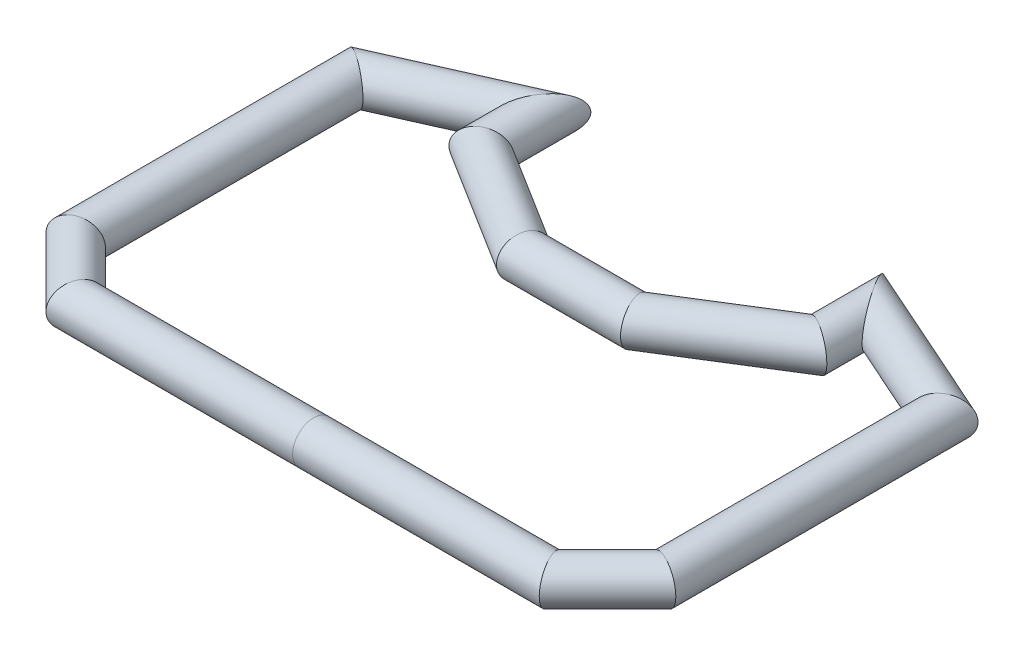
SolidWorks part; units mm, degrees
ref_plane "Front Plane" through (0, 0, 0) normal (0, 0, 1) x (1, 0, 0)
ref_plane "Top Plane" through (0, 0, 0) normal (0, 1, 0) x (1, 0, 0)
ref_plane "Right Plane" through (0, 0, 0) normal (1, 0, 0) x (0, 0, -1)
sketch "Sketch1" plane through (0, 0, 0) normal (0, 1, 0) x (1, 0, 0)
  line L0 (-266.7, -373.8736) -> (-266.7, -119.8736) construction
  line L1 (-152.4, -69.0736) -> (-266.7, -119.8736) construction
  line L2 (-215.9, -424.6736) -> (-266.7, -373.8736) construction
  line L3 (-215.9, -424.6736) -> (215.9, -424.6736) construction
  line L4 (215.9, -424.6736) -> (266.7, -373.8736) construction
  line L5 (266.7, -373.8736) -> (266.7, -119.8736) construction
  line L6 (266.7, -119.8736) -> (152.4, -69.0736) construction
  line L7 (152.4, -69.0736) -> (152.4, -119.8736) construction
  line L8 (152.4, -119.8736) -> (50.8, -183.3736) construction
  line L9 (50.8, -183.3736) -> (-50.8, -183.3736) construction
  line L10 (-152.4, -119.8736) -> (-50.8, -183.3736) construction
  line L11 (-152.4, -69.0736) -> (-152.4, -119.8736) construction
  line L12 (-266.7, -373.8736) -> (-266.7, -119.8736)
  line L13 (-152.4, -69.0736) -> (-266.7, -119.8736)
  line L14 (-215.9, -424.6736) -> (-266.7, -373.8736)
  line L15 (-215.9, -424.6736) -> (215.9, -424.6736)
  line L16 (215.9, -424.6736) -> (266.7, -373.8736)
  line L17 (266.7, -373.8736) -> (266.7, -119.8736)
  line L18 (266.7, -119.8736) -> (152.4, -69.0736)
  line L19 (152.4, -69.0736) -> (152.4, -119.8736)
  line L20 (152.4, -119.8736) -> (50.8, -183.3736)
  line L21 (50.8, -183.3736) -> (-50.8, -183.3736)
  line L22 (-152.4, -119.8736) -> (-50.8, -183.3736)
  line L23 (-152.4, -69.0736) -> (-152.4, -119.8736)
sketch "Sketch2" plane through (0, 0, 0) normal (1, 0, 0) x (0, 0, -1)
  circle A0 centre (-424.6736, 0) radius 19.05
  dimension "D1" = 38.1
sweep "Sweep1" add profiles "Sketch2" path "Sketch1"
